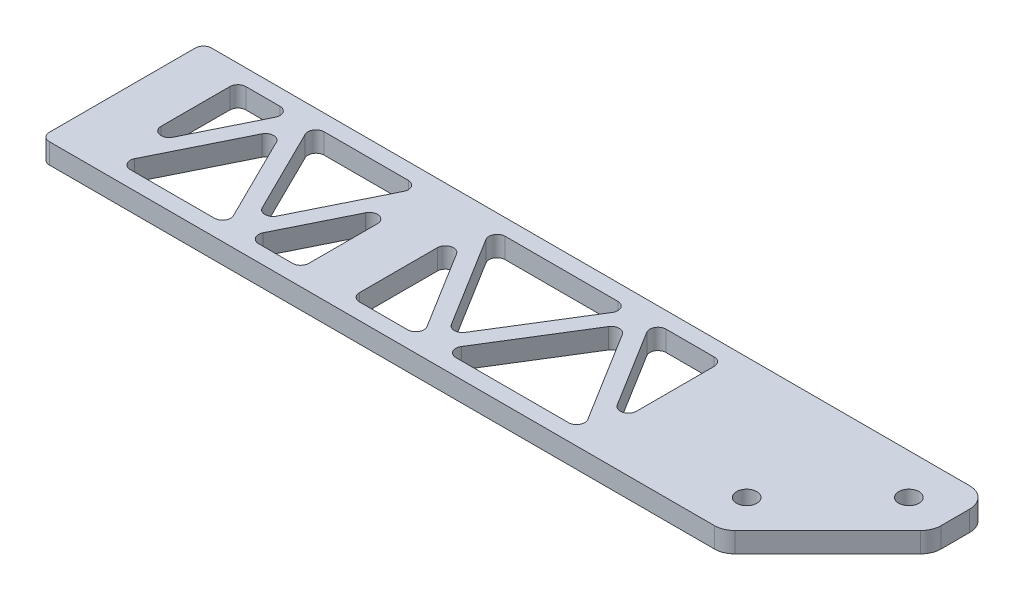
SolidWorks part; units mm, degrees
ref_plane "Front Plane" through (0, 0, 0) normal (0, 0, 1) x (1, 0, 0)
ref_plane "Top Plane" through (0, 0, 0) normal (0, 1, 0) x (1, 0, 0)
ref_plane "Right Plane" through (0, 0, 0) normal (1, 0, 0) x (0, 0, -1)
sketch "Sketch1" plane through (0, 0, 0) normal (0, 1, 0) x (1, 0, 0)
  line L0 (121.4655, -25.4) -> (172.2655, 25.4)
  line L1 (-92.075, 25.4) -> (172.2655, 25.4)
  line L2 (-92.075, 25.4) -> (-92.075, -25.4)
  line L3 (-92.075, -25.4) -> (121.4655, -25.4)
  line L5 (81.915, 25.4) -> (81.915, -25.4)
  line L6 (-76.2, 20.32) -> (-15.875, 20.32)
  line L7 (-76.2, 20.32) -> (-76.2, -20.32)
  line L8 (-76.2, -20.32) -> (-15.875, -20.32)
  line L9 (-15.875, 20.32) -> (-15.875, -20.32)
  line L10 (0, 20.32) -> (75.565, 20.32)
  line L11 (0, 20.32) -> (0, -20.32)
  line L12 (0, -20.32) -> (75.565, -20.32)
  line L13 (75.565, 20.32) -> (75.565, -20.32)
  line L14 (-76.2, -20.32) -> (-56.0917, 20.32)
  line L15 (-56.0917, 20.32) -> (-35.9833, -20.32)
  line L16 (-35.9833, -20.32) -> (-15.875, 20.32)
  line L17 (116.205, -12.7) -> (141.605, 12.7) construction
  line L18 (0, 20.32) -> (25.1883, -20.32)
  line L19 (25.1883, -20.32) -> (50.3767, 20.32)
  line L20 (50.3767, 20.32) -> (75.565, -20.32)
  line L21 (-73.9234, -21.4464) -> (-56.0917, 14.5925)
  line L22 (-56.0917, 14.5925) -> (-35.9833, -26.0475)
  line L23 (-35.9833, -26.0475) -> (-13.5984, 19.1936)
  line L24 (-2.159, 18.9819) -> (25.1883, -25.1415)
  line L25 (25.1883, -25.1415) -> (50.3767, 15.4985)
  line L26 (50.3767, 15.4985) -> (73.406, -21.6581)
  line L27 (-78.4766, -19.1936) -> (-56.0917, 26.0475)
  line L28 (-56.0917, 26.0475) -> (-35.9833, -14.5925)
  line L29 (-35.9833, -14.5925) -> (-18.1516, 21.4464)
  line L30 (2.159, 21.6581) -> (25.1883, -15.4985)
  line L31 (25.1883, -15.4985) -> (50.3767, 25.1415)
  line L32 (50.3767, 25.1415) -> (77.724, -18.9819)
  line L33 (154.305, 7.4395) -> (154.305, 25.4)
  circle A0 centre (141.605, 12.7) radius 3.175
  circle A1 centre (116.205, -12.7) radius 3.175
  point P6 (0, 0)
  point P19 (-15.875, 0)
  point P42 (-92.075, 0)
  dimension "D5" = 6.35
  dimension "D9" = 6.35
  dimension "D2" = 76.2
  dimension "D3" = 15.875
  dimension "D4" = 5.08
  dimension "D6" = 75.565
  dimension "D7" = 15.875
  dimension "D8" = 50.8
  dimension "D10" = 25.4
  dimension "D11" = 2.54
  dimension "D13" = 12.7
  dimension "D14" = 81.915
  dimension "D15" = 34.29
  dimension "D16" = 12.7
  dimension "D17" = 12.7
  dimension "D18" = 12.7
  dimension "D12" = 2.54
extrude "Boss-Extrude1" add sketch "Sketch1" along normal mid plane 6.35
fillet "Fillet1" radius 2.54 26 edges at (-92.075, 0, -25.4) (-92.075, 0, 25.4) (2.9883, 0, -20.32) (25.1883, 0, 15.4985) (47.3884, 0, -20.32) (0, 0, -15.4985) (0, 0, 20.32) (22.2, 0, 20.32) (72.5767, 0, 20.32) (50.3767, 0, -15.4985) (28.1766, 0, 20.32) (75.565, 0, 15.4985) (75.565, 0, -20.32) (53.365, 0, -20.32) (-76.2, 0, -20.32) (-76.2, 0, 14.5925) (-58.9256, 0, -20.32) (-73.3661, 0, 20.32) (-38.8172, 0, 20.32) (-15.875, 0, 20.32) (-15.875, 0, -14.5925) (-33.1494, 0, 20.32) (-35.9833, 0, 14.5925) (-18.7089, 0, -20.32) (-53.2578, 0, -20.32) (-56.0917, 0, -14.5925)
fillet "Fillet2" radius 6.35 3 edges at (154.305, 0, -25.4) (154.305, 0, -7.4395) (121.4655, 0, 25.4)
move or copy body "Body-Move/Copy1" [suppressed] bodies to move or copy 101 parameters "D1"=0, "D2"=0, "D3"=0
